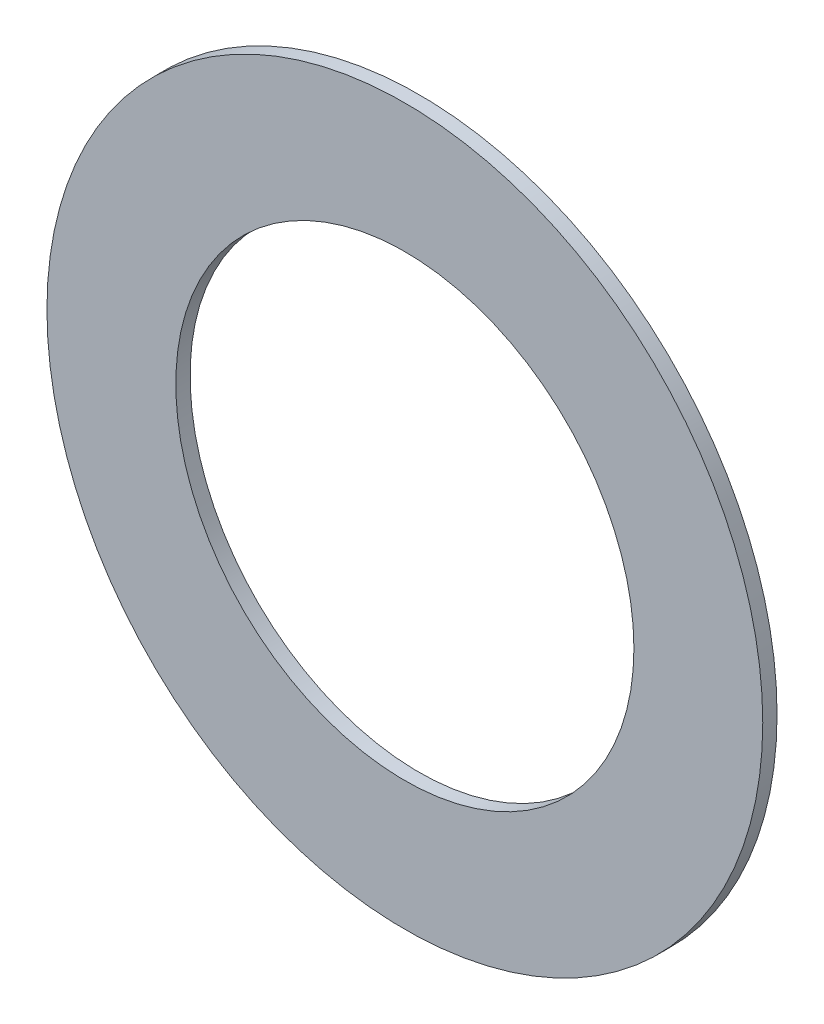
SolidWorks part; units mm, degrees
material "AISI 1035 Steel (SS)"
ref_plane "Front Plane" through (0, 0, 0) normal (0, 0, 1) x (1, 0, 0)
ref_plane "Top Plane" through (0, 0, 0) normal (0, 1, 0) x (1, 0, 0)
ref_plane "Right Plane" through (0, 0, 0) normal (1, 0, 0) x (0, 0, -1)
sketch "Sketch1" plane through (0, 0, 0) normal (0, 0, 1) x (1, 0, 0)
  circle A0 centre (0, 0) radius 19.8438
  circle A1 centre (0, 0) radius 12.7
  dimension "D1" = 25.4
  dimension "D2" = 39.6875
extrude "Boss-Extrude1" add sketch "Sketch1" along normal blind 0.7925
